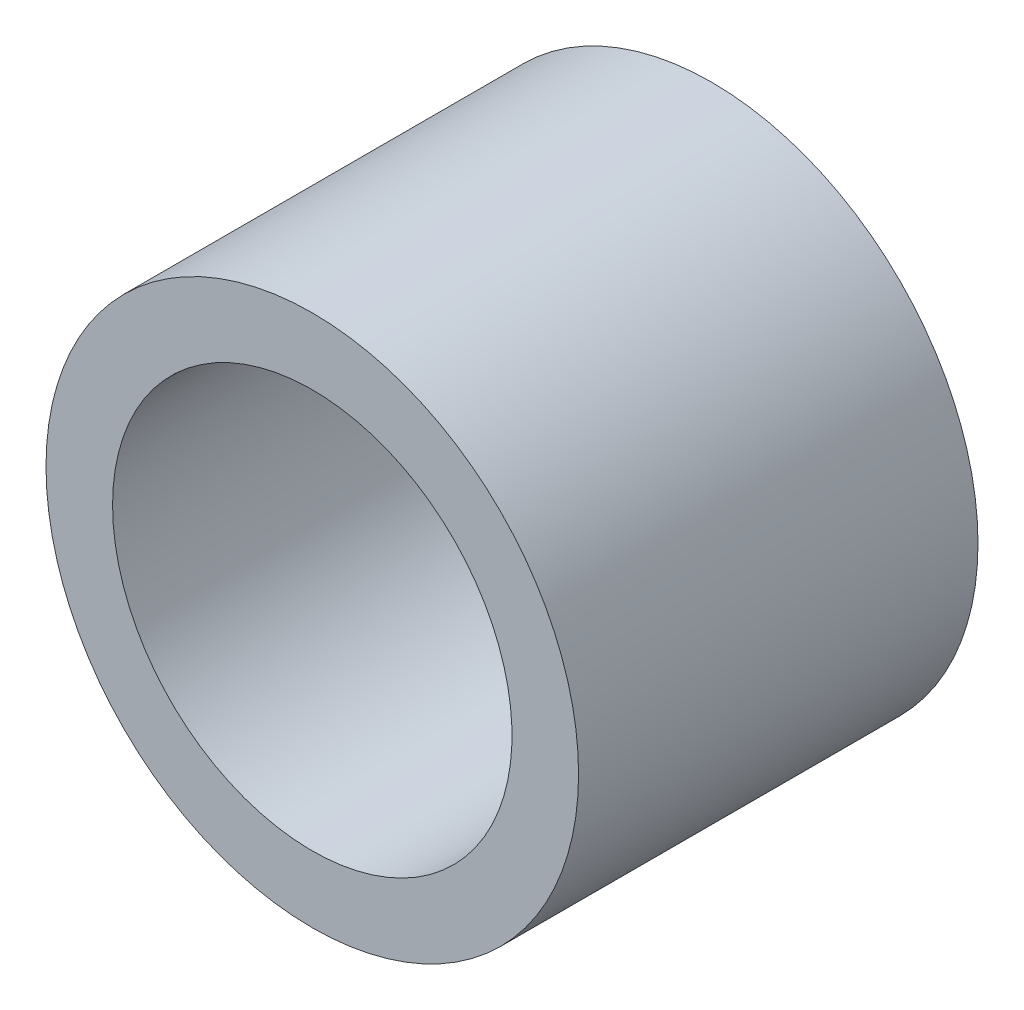
SolidWorks part; units mm, degrees
material "Nylon 101"
ref_plane "Front Plane" through (0, 0, 0) normal (0, 0, 1) x (1, 0, 0)
ref_plane "Top Plane" through (0, 0, 0) normal (0, 1, 0) x (1, 0, 0)
ref_plane "Right Plane" through (0, 0, 0) normal (1, 0, 0) x (0, 0, -1)
sketch "Sketch1" plane through (0, 0, 0) normal (0, 0, 1) x (1, 0, 0)
  circle A0 centre (0, 0) radius 4.7625
  circle A1 centre (0, 0) radius 6.35
  dimension "D1" = 12.7
  dimension "D2" = 9.525
extrude "Boss-Extrude1" add sketch "Sketch1" along normal blind 9.525
